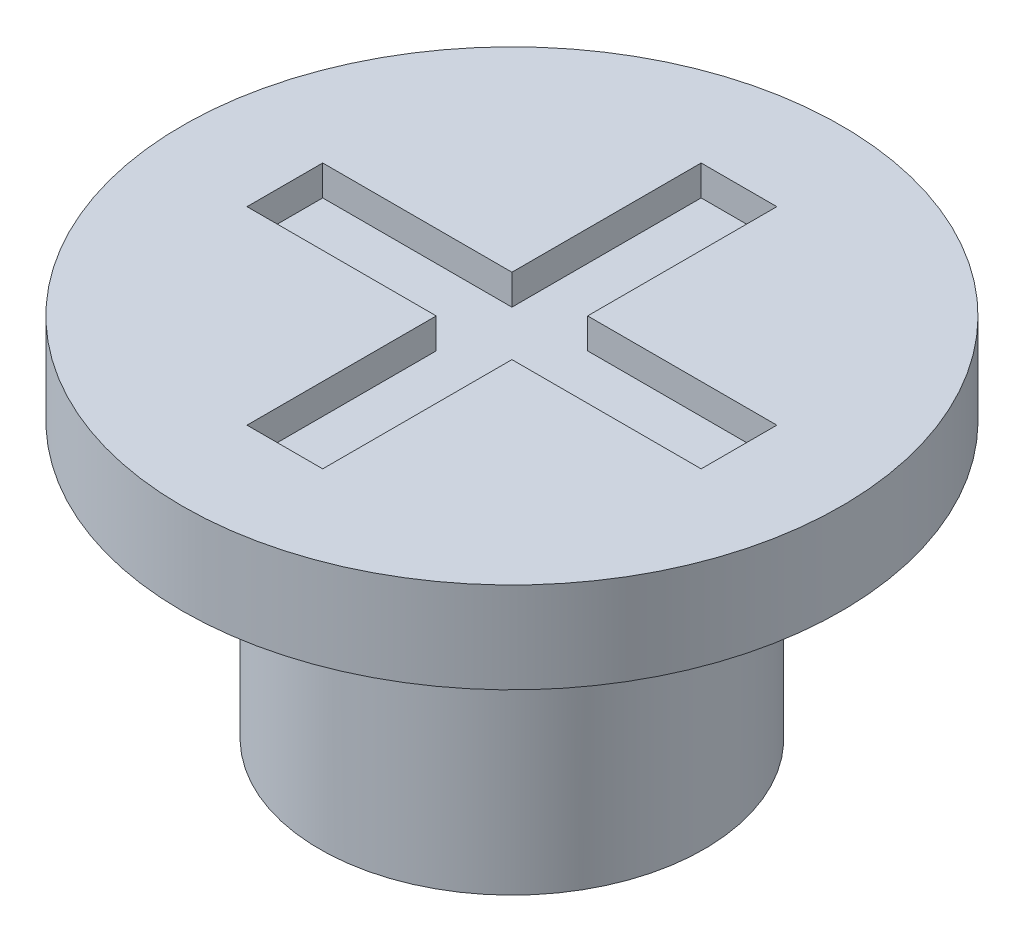
SolidWorks part; units mm, degrees
ref_plane "Front Plane" through (0, 0, 0) normal (0, 0, 1) x (1, 0, 0)
ref_plane "Top Plane" through (0, 0, 0) normal (0, 1, 0) x (1, 0, 0)
ref_plane "Right Plane" through (0, 0, 0) normal (1, 0, 0) x (0, 0, -1)
sketch "Sketch1" plane through (0, 0, 0) normal (0, 1, 0) x (1, 0, 0)
  circle A0 centre (0, 0) radius 3.175
  dimension "D1" = 6.35
extrude "Boss-Extrude1" add sketch "Sketch1" along normal blind 21.54
sketch "Sketch2" plane through (0, 21.54, 0) normal (0, 1, 0) x (1, 0, 0)
  circle A0 centre (0, 0) radius 5.4429
  dimension "D1" = 10.8857
extrude "Boss-Extrude2" add sketch "Sketch2" along normal blind 1.5
sketch "Sketch3" plane through (0, 23.04, 0) normal (0, 1, 0) x (1, 0, 0)
  line L0 (0, 0) -> (0, 5.4429) construction
  line L1 (0, 5.4429) -> (0, -5.4429) construction
  line L2 (-5.4429, 0) -> (5.4429, 0) construction
  line L4 (-0.625, -3.75) -> (0.625, -3.75)
  line L5 (-0.625, -3.75) -> (-0.625, 3.75)
  line L6 (-0.625, 3.75) -> (0.625, 3.75)
  line L7 (0.625, -3.75) -> (0.625, 3.75)
  line L8 (-0.625, -3.75) -> (0.625, 3.75) construction
  line L9 (-0.625, 3.75) -> (0.625, -3.75) construction
  line L10 (3.75, -0.625) -> (-3.75, -0.625)
  line L11 (3.75, -0.625) -> (3.75, 0.625)
  line L12 (3.75, 0.625) -> (-3.75, 0.625)
  line L13 (-3.75, -0.625) -> (-3.75, 0.625)
  line L14 (3.75, -0.625) -> (-3.75, 0.625) construction
  line L15 (3.75, 0.625) -> (-3.75, -0.625) construction
  circle A0 centre (0, 0) radius 5.4429 construction
  dimension "D1" = 7.5
  dimension "D2" = 1.25
extrude "Cut-Extrude2" cut sketch "Sketch3" against normal blind 0.5 contours L7 L10 L5 L4 | L13 L10 L5 L12 | L12 L7 L6 L5 | L11 L12 L7 L10 | L7 L12 L5 L10
sketch "Sketch4" plane through (0, 0, 0) normal (0, -1, 0) x (1, 0, 0)
  circle A0 centre (0, 0) radius 3.175
  point P3 (0, 0)
extrude "Cut-Extrude3" cut sketch "Sketch4" against normal blind 17
